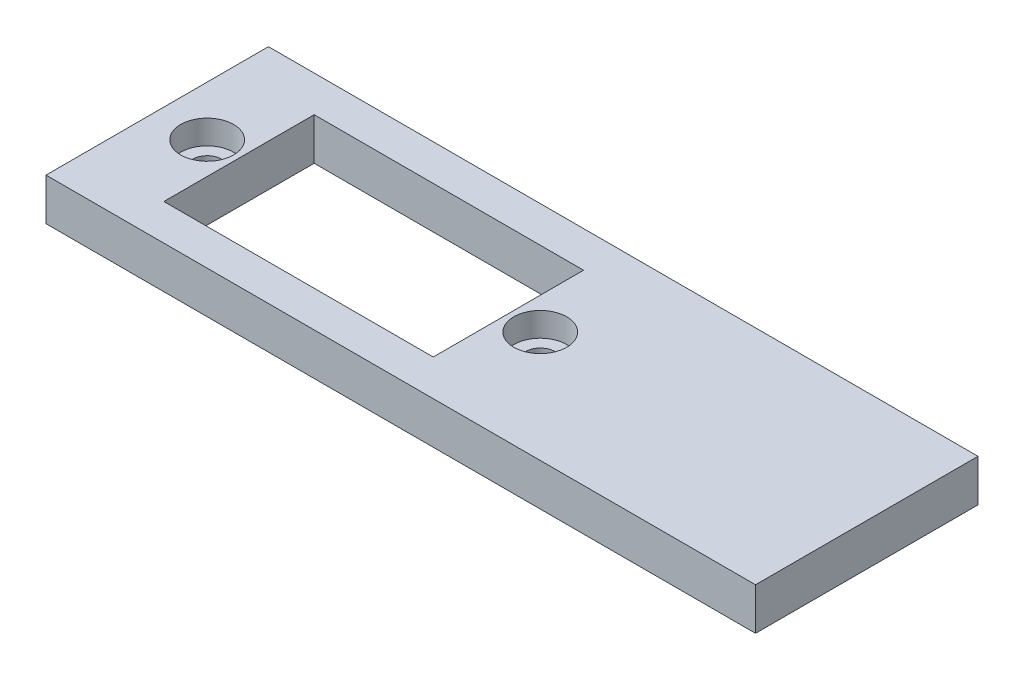
SolidWorks part; units mm, degrees
ref_plane "Front" through (0, 0, 0) normal (0, 0, 1) x (1, 0, 0)
ref_plane "Top" through (0, 0, 0) normal (0, 1, 0) x (1, 0, 0)
ref_plane "Right" through (0, 0, 0) normal (1, 0, 0) x (0, 0, -1)
sketch "草图1" plane through (0, 0, 0) normal (0, 1, 0) x (1, 0, 0)
  line L0 (0, 9.25) -> (0, -9.25) construction
  line L1 (-36, -9.25) -> (0, -9.25)
  line L2 (-36, -9.25) -> (-36, 9.25)
  line L3 (-36, 9.25) -> (0, 9.25)
  line L5 (-36, -9.25) -> (0, 0) construction
  line L6 (-36, 9.25) -> (0, 0) construction
  line L7 (-36, 0) -> (0, 0) construction
  line L8 (-18, 9.25) -> (-18, -9.25) construction
  line L9 (0, -9.25) -> (23, -9.25)
  line L10 (-6.8, 6.25) -> (-29.2, 6.25)
  line L11 (-6.8, 6.25) -> (-6.8, -6.25)
  line L12 (-6.8, -6.25) -> (-29.2, -6.25)
  line L13 (-29.2, 6.25) -> (-29.2, -6.25)
  line L14 (-6.8, 6.25) -> (-29.2, -6.25) construction
  line L15 (-6.8, -6.25) -> (-29.2, 6.25) construction
  line L17 (0, 9.25) -> (23, 9.25)
  line L18 (23, -9.25) -> (23, 9.25)
  point P0 (0, 0)
  point P12 (-18, 0)
  dimension "D1" = 23
  dimension "D2" = 18.5
  dimension "D3" = 18
  dimension "D4" = 22.4
  dimension "D5" = 12.5
extrude "凸台-拉伸1" add sketch "草图1" along normal blind 3.5
sketch "草图2" plane through (0, 3.5, 0) normal (0, 1, 0) x (1, 0, 0)
  line L0 (-36, 0) -> (0, 0) construction
  line L3 (-18, 6.25) -> (-18, -6.25) construction
  line L4 (-6.8, 6.25) -> (-29.2, 6.25) construction
  line L5 (-29.2, -6.25) -> (-6.8, -6.25) construction
  line L6 (-36, 9.25) -> (-36, -9.25) construction
  point P6 (-31.85, 0)
  point P7 (-4.15, 0)
  dimension "D1" = 27.7
  dimension "D3" = 13.85
hole_wizard "M2 凹头盖螺钉的柱形沉头孔2" positions "3D草图2" profile "草图5" counterbore size "M2" standard "ANSI Metric" end condition up to next
sketch3d "3D草图2"
  point P0 (-31.85, 3.5, 0)
  point P3 (-4.15, 3.5, 0)
sketch "草图5" plane through (-31.85, 3.5, 0) normal (1, 0, 0) x (0, 0, 1)
  line L0 (0, 0) -> (0, 3.5)
  line L1 (0, 3.5) -> (1.2, 3.5)
  line L3 (1.2, 3.5) -> (1.2, 2)
  line L4 (1.2, 2) -> (2.2, 2)
  line L5 (2.2, 2) -> (2.2, 0)
  line L7 (2.2, 0) -> (0, 0)
  line L11 (0, -6.35) -> (0, 107.95) construction
  dimension "通孔孔直径" = 2.4
  dimension "通孔孔深度" = 3.5
  dimension "柱形沉头孔直径" = 4.4
  dimension "柱形沉头孔深度" = 2
